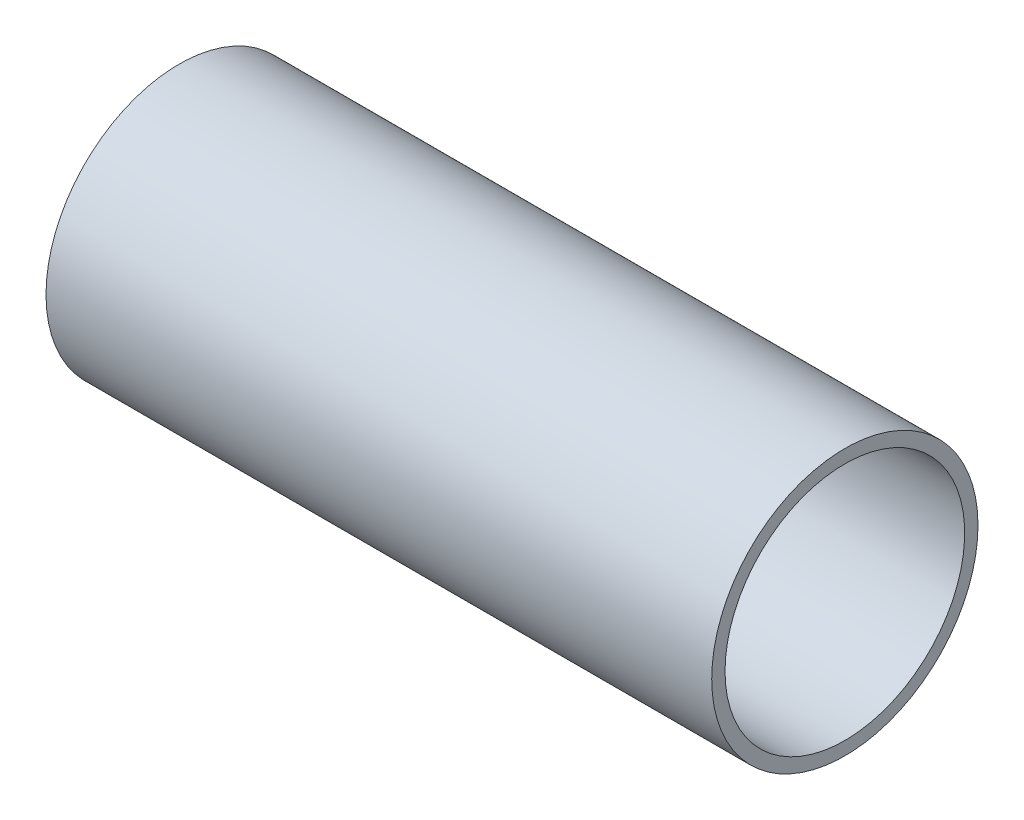
SolidWorks part; units mm, degrees
ref_plane "Front Plane" through (0, 0, 0) normal (0, 0, 1) x (1, 0, 0)
ref_plane "Top Plane" through (0, 0, 0) normal (0, 1, 0) x (1, 0, 0)
ref_plane "Right Plane" through (0, 0, 0) normal (1, 0, 0) x (0, 0, -1)
sketch "Sketch2" plane through (0, 0, 0) normal (1, 0, 0) x (0, 0, -1)
  circle A0 centre (0, 0) radius 228.6
  circle A1 centre (0, 0) radius 254
  dimension "D1" = 457.2
  dimension "D2" = 508
extrude "Boss-Extrude1" add sketch "Sketch2" along normal mid plane 1270
